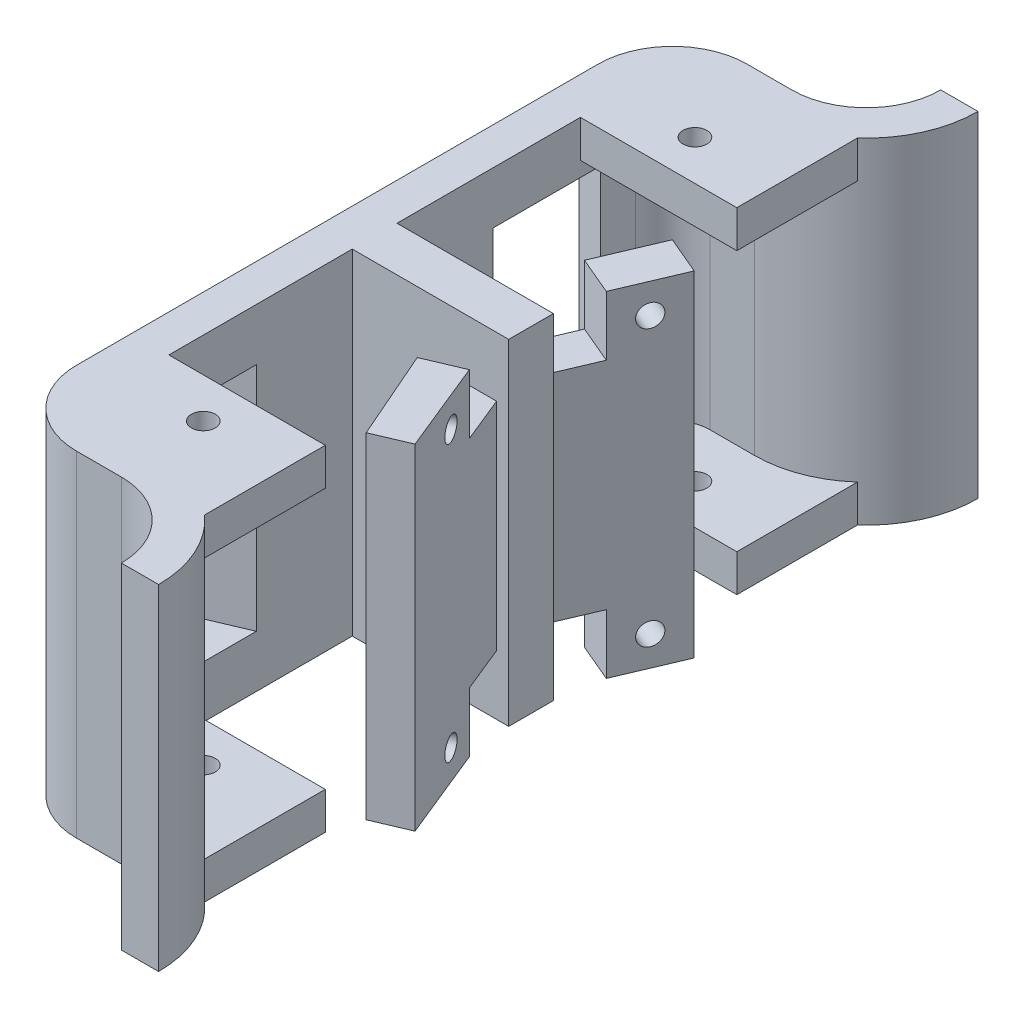
SolidWorks part; units mm, degrees
ref_plane "前视基准面" through (0, 0, 0) normal (0, 0, 1) x (1, 0, 0)
ref_plane "上视基准面" through (0, 0, 0) normal (0, 1, 0) x (1, 0, 0)
ref_plane "右视基准面" through (0, 0, 0) normal (1, 0, 0) x (0, 0, -1)
sketch "草图1" plane through (0, 0, 0) normal (0, 1, 0) x (1, 0, 0)
  line L0 (0, 0) -> (27.7625, 0) construction
  line L1 (26, 55) -> (31, 55)
  line L2 (10, 40) -> (16, 40)
  line L3 (0, 35) -> (0, -35)
  line L4 (10, -45) -> (16, -45)
  line L5 (10, 45) -> (16, 45)
  line L8 (5, 35) -> (5, -35)
  line L9 (10, -40) -> (16, -40)
  line L10 (26, -55) -> (31, -55)
  arc A0 (0, -35) -> (10, -45) centre (10, -35) ccw
  arc A1 (16, 40) -> (31, 55) centre (16, 55) ccw
  arc A2 (16, -45) -> (26, -55) centre (16, -55) cw
  arc A3 (5, 35) -> (10, 40) centre (10, 35) cw
  arc A4 (5, -35) -> (10, -40) centre (10, -35) ccw
  arc A5 (16, -40) -> (31, -55) centre (16, -55) cw
  arc A6 (16, 45) -> (26, 55) centre (16, 55) ccw
  arc A7 (0, 35) -> (10, 45) centre (10, 35) cw
  point P19 (5, 0)
extrude "凸台-拉伸1" add sketch "草图1" along normal blind 45
ref_plane "基准面1" through (0, 0, 0) normal (0, -1, 0) x (-1, 0, 0)
ref_plane "基准面2" through (5, 0, 0) normal (1, 0, 0) x (0, 0, -1)
sketch "草图2" plane through (5, 0, 0) normal (1, 0, 0) x (0, 0, -1)
  line L0 (0, 0) -> (0, 45) construction
  line L2 (33, 45) -> (33, 0) construction
  line L3 (-35, 45) -> (35, 45) construction
  line L4 (-17.05, 0) -> (17.05, 0) construction
ref_plane "基准面3" through (0, 45, 0) normal (0, 1, 0) x (1, 0, 0)
sketch "草图3" plane through (0, 45, 0) normal (0, 1, 0) x (1, 0, 0)
  line L0 (0, 0) -> (56.6452, 0) construction
  line L1 (5, -35) -> (5, 35) construction
  line L2 (5, 27.6232) -> (26, 27.6232)
  line L3 (26, 27.6232) -> (26, 55)
  line L4 (16, 45) -> (10, 45)
  line L5 (0, 35) -> (0, 27.6232)
  line L6 (0, 35) -> (0, -35) construction
  line L7 (0, 27.6232) -> (5, 27.6232)
  line L8 (0, -27.6232) -> (5, -27.6232)
  line L9 (0, -35) -> (0, -27.6232)
  line L10 (16, -45) -> (10, -45)
  line L11 (26, -27.6232) -> (26, -55)
  line L12 (5, -27.6232) -> (26, -27.6232)
  arc A0 (16, 45) -> (26, 55) centre (16, 55) ccw construction
  arc A1 (26, 55) -> (16, 45) centre (16, 55) cw
  arc A2 (10, 45) -> (0, 35) centre (10, 35) ccw
  arc A3 (10, -45) -> (0, -35) centre (10, -35) cw
  arc A4 (26, -55) -> (16, -45) centre (16, -55) ccw
extrude "凸台-拉伸2" add sketch "草图3" against normal blind 5
ref_plane "基准面4" through (0, 22.5, 0) normal (0, -1, 0) x (-1, 0, 0)
sketch "草图4" plane through (0, 22.5, 0) normal (0, -1, 0) x (-1, 0, 0)
  line L0 (-40.4237, 58.803) -> (15.6757, 58.803)
  line L1 (15.6757, 58.803) -> (15.6757, -58.2961)
  line L2 (15.6757, -58.2961) -> (-40.4237, -58.2961)
  line L3 (-40.4237, -58.2961) -> (-40.4237, 58.803)
extrude "切除-拉伸1" cut sketch "草图4" along normal through all
mirror "镜向5" about plane through (0, 22.5, 0) normal (0, 1, 0) of "凸台-拉伸1", "凸台-拉伸2"
ref_plane "基准面5" through (0, 0, 0) normal (-1, 0, 0) x (0, 0, 1)
sketch "草图8" plane through (0, 0, 0) normal (0, -1, 0) x (-1, 0, 0)
  line L0 (-5, 33) -> (-15, 33) construction
  line L1 (0, 0) -> (-55.3859, 0) construction
  circle A0 centre (-15, 33) radius 1.6
  circle A1 centre (-15, -33) radius 1.6
  point P3 (26.4846, -29.7603)
extrude "切除-拉伸3" cut sketch "草图8" against normal through all
sketch "草图10" plane through (0, 0, 0) normal (-1, 0, 0) x (0, 0, 1)
  line L1 (17.05, 45) -> (-17.05, 45) construction
  line L2 (3, 45) -> (3, 0)
  line L3 (-55, 0) -> (55, 0) construction
  line L4 (3, 0) -> (-3, 0)
  line L5 (-3, 0) -> (-3, 45)
  line L6 (-3, 45) -> (3, 45)
extrude "凸台-拉伸5" add sketch "草图10" against normal blind 26
sketch "草图11" plane through (0, 45, 0) normal (0, 1, 0) x (1, 0, 0)
  line L1 (0, 24.75) -> (0, -24.75) construction
  line L3 (0, 35) -> (0, 38)
  line L5 (0, 35) -> (21.1716, 26.0132)
  line L6 (0, 35) -> (0, 18)
  line L8 (21.1716, 9.0132) -> (0, 18)
  line L9 (21.1716, 26.0132) -> (21.1716, 9.0132)
  arc A0 (10, 45) -> (0, 35) centre (10, 35) ccw construction
ref_plane "基准面6" through (0, 38, 0) normal (0, 1, 0) x (1, 0, 0)
sketch "孔草图" plane through (0, 38, 0) normal (0, 1, 0) x (1, 0, 0)
  line L4 (0, 0) -> (44.6308, 0) construction
  line L5 (0, -18) -> (0, -35)
  line L6 (0, -35) -> (21.1716, -26.0132)
  line L7 (21.1716, -26.0132) -> (21.1716, -9.0132)
  line L8 (21.1716, -9.0132) -> (0, -18)
  line L13 (0, 35) -> (0, 18) construction
  line L14 (0, 32.4486) -> (0, 18)
  line L16 (0, 32.4486) -> (21.1716, 23.4618)
  line L17 (21.1716, 23.4618) -> (15.9749, 11.2191)
  line L18 (0, 18) -> (15.9749, 11.2191)
extrude "切除-拉伸4" cut sketch "孔草图" against normal blind 31
sketch "草图14" plane through (0, 0, 0) normal (0, -1, 0) x (-1, 0, 0)
  line L0 (0, 18) -> (-6.1144, 32.4046)
  line L1 (0, 35) -> (-21.1716, 26.0132) construction
  line L2 (-6.1144, 32.4046) -> (-27.286, 23.4178)
  line L3 (-27.286, 23.4178) -> (-21.1716, 9.0132)
  line L4 (-21.1716, 9.0132) -> (0, 18)
sketch "草图15" plane through (0, 0, 0) normal (0, -1, 0) x (-1, 0, 0)
  line L2 (-26, 3) -> (-5, 3) construction
  line L3 (-18.373, 3) -> (-24.373, 3)
  line L7 (-10.5858, 27.9552) -> (-35.1763, 17.5172) construction
  line L8 (0, 0) -> (-68.6607, 0) construction
  line L9 (-31.8885, -21.4641) -> (-24.373, -3)
  line L10 (-27.286, -23.4178) -> (-31.8885, -21.4641)
  line L11 (-18.373, -3) -> (-27.286, -23.4178)
  line L12 (-18.373, -3) -> (-24.373, -3)
  line L13 (0, 32.4486) -> (-21.1716, 23.4618) construction
  line L16 (-18.373, 3) -> (-25.4062, 19.5691)
  line L17 (-25.4062, 19.5691) -> (-30.4902, 17.4111)
  line L18 (-30.4902, 17.4111) -> (-24.373, 3)
extrude "凸台-拉伸6" add sketch "草图15" against normal blind 45
sketch "草图16" plane through (0, 0, 0) normal (0, -1, 0) x (-1, 0, 0)
  line L2 (-24.373, -3) -> (-18.373, -3)
  line L4 (-26.9736, -9.1265) -> (-24.373, -3)
  line L6 (0, 0) -> (-69.6422, 0) construction
  line L11 (-25.4062, 19.5691) -> (-21.8896, 11.2845) construction
  line L12 (-18.373, 3) -> (-25.4062, 19.5691) construction
  line L13 (-18.373, 3) -> (-21.8896, 11.2845)
  line L14 (-21.8896, 11.2845) -> (-26.9736, 9.1265)
  line L15 (-30.4902, 17.4111) -> (-24.373, 3) construction
  line L16 (-26.9736, 9.1265) -> (-24.373, 3)
  line L17 (-24.373, 3) -> (-18.373, 3)
  line L18 (-21.8896, -11.2845) -> (-26.9736, -9.1265)
  line L19 (-18.373, -3) -> (-21.8896, -11.2845)
extrude "切除-拉伸6" cut sketch "草图16" against normal blind 8
mirror "镜向6" about plane through (0, 22.5, 0) normal (0, -1, 0) of "切除-拉伸6"
ref_plane "基准面7" through (19.573, 0, 8.3082) normal (0.9205, 0, 0.3907) x (0.3907, 0, -0.9205)
sketch "草图19" plane through (19.573, 0, 8.3082) normal (0.9205, 0, 0.3907) x (0.3907, 0, -0.9205)
  line L0 (23.4404, 45) -> (23.4404, 41) construction
  line L1 (27.9404, 45) -> (18.9404, 45) construction
  line L2 (23.4404, 0) -> (23.4404, 4) construction
  circle A0 centre (23.4404, 41) radius 1.5
  circle A1 centre (23.4404, 4) radius 1.5
extrude "切除-拉伸7" cut sketch "草图19" against normal up to next
ref_plane "基准面8" through (0, 0, 0) normal (0, 0, 1) x (1, 0, 0)
mirror "镜向7" about plane through (0, 0, 0) normal (0, 0, 1) of "切除-拉伸7"
